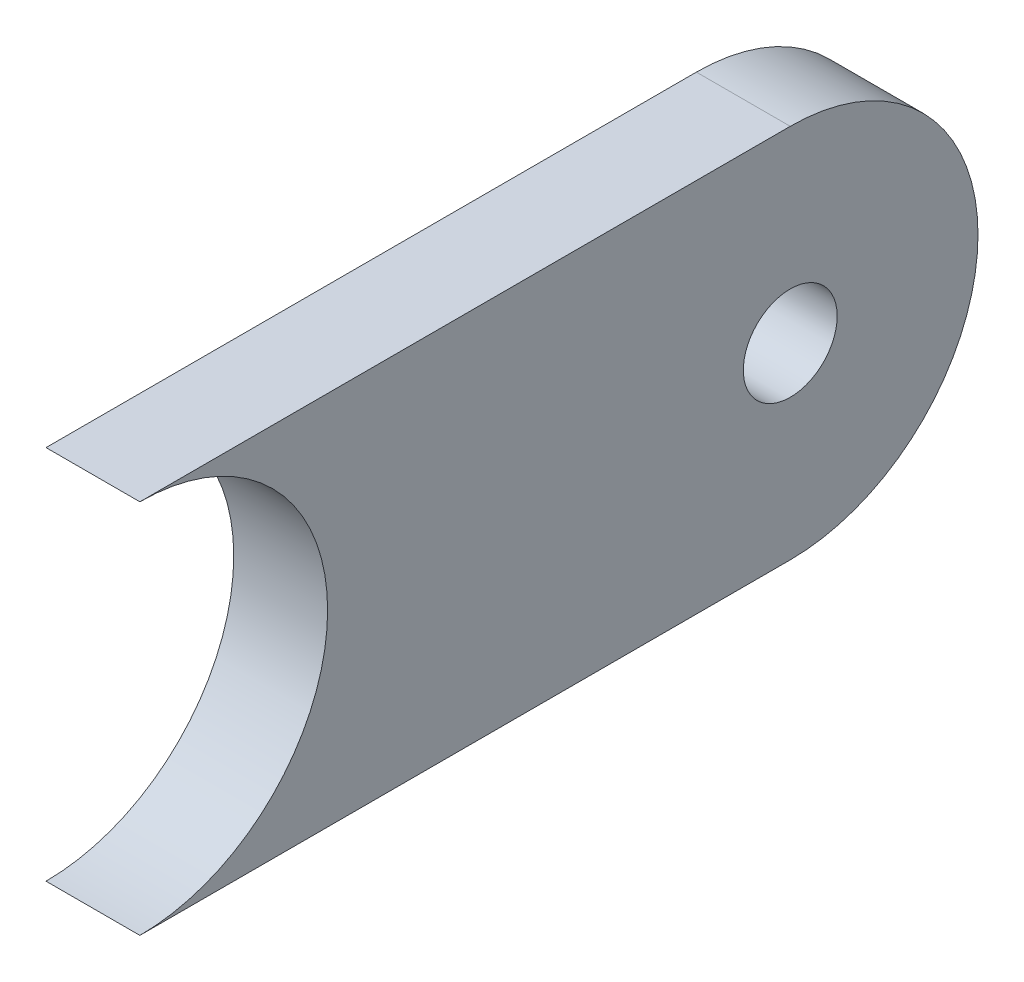
SolidWorks part; units mm, degrees
ref_plane "前基準面" through (0, 0, 0) normal (0, 0, 1) x (1, 0, 0)
ref_plane "上基準面" through (0, 0, 0) normal (0, 1, 0) x (1, 0, 0)
ref_plane "右基準面" through (0, 0, 0) normal (1, 0, 0) x (0, 0, -1)
sketch "草圖1" plane through (0, 0, 0) normal (1, 0, 0) x (0, 0, -1)
  line L0 (-34.64, -10) -> (0, -10)
  line L1 (-34.64, 10) -> (0, 10)
  circle A0 centre (0, 0) radius 2.5
  arc A1 (0, -10) -> (0, 10) centre (0, 0) ccw
  arc A2 (-34.64, -10) -> (-34.64, 10) centre (-34.64, 0) ccw
  dimension "D1" = 20
  dimension "D2" = 5
  dimension "D3" = 20
  dimension "D4" = 34.64
extrude "填料-伸長1" add sketch "草圖1" along normal blind 5
